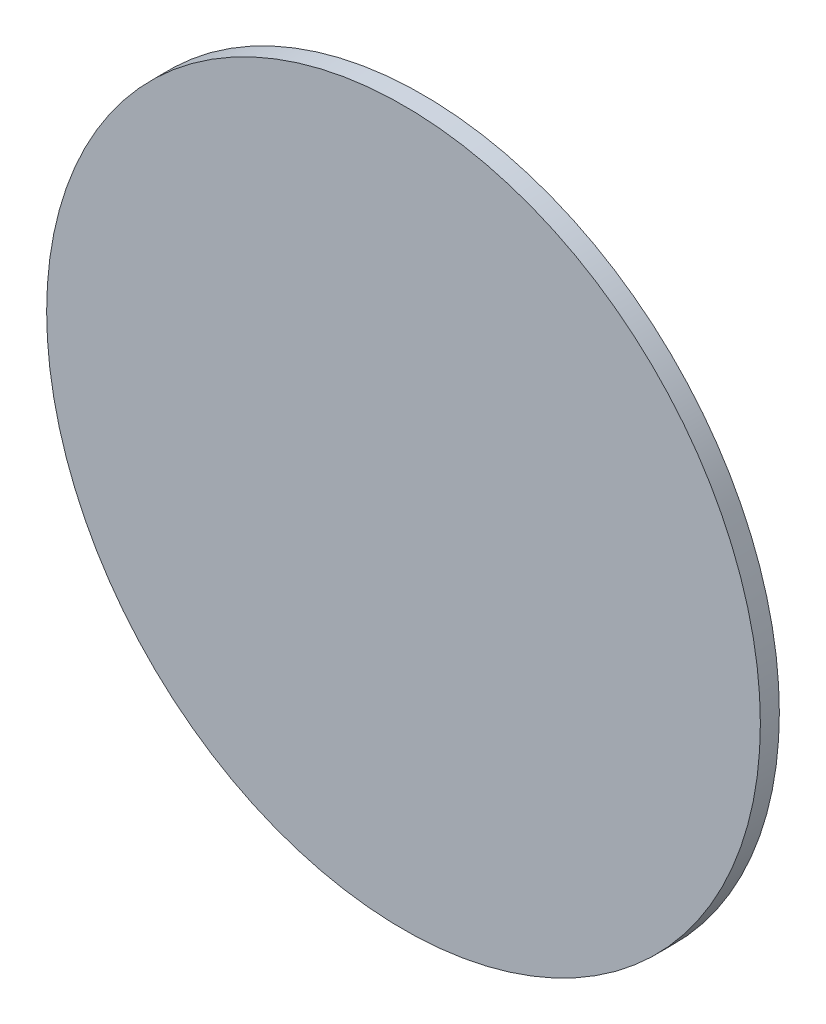
SolidWorks part; units mm, degrees
ref_plane "Front Plane" through (0, 0, 0) normal (0, 0, 1) x (1, 0, 0)
ref_plane "Top Plane" through (0, 0, 0) normal (0, 1, 0) x (1, 0, 0)
ref_plane "Right Plane" through (0, 0, 0) normal (1, 0, 0) x (0, 0, -1)
sketch "Sketch1" plane through (0, 0, 0) normal (0, 0, 1) x (1, 0, 0)
  circle A0 centre (0, 0) radius 18.8
  dimension "D1" = 37.6
extrude "Boss-Extrude1" add sketch "Sketch1" along normal blind 1
